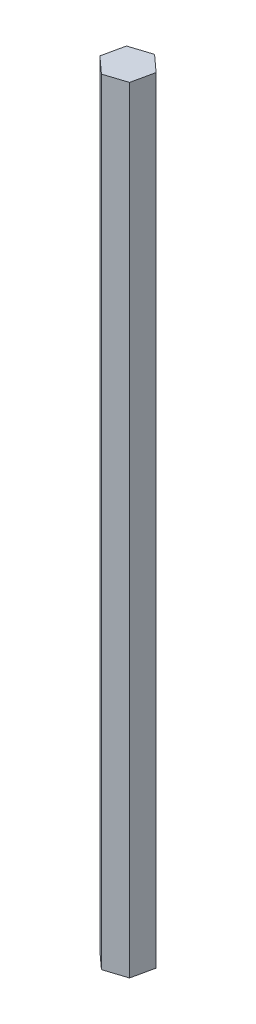
SolidWorks part; units mm, degrees
ref_plane "Front Plane" through (0, 0, 0) normal (0, 0, 1) x (1, 0, 0)
ref_plane "Top Plane" through (0, 0, 0) normal (0, 1, 0) x (1, 0, 0)
ref_plane "Right Plane" through (0, 0, 0) normal (1, 0, 0) x (0, 0, -1)
sketch "Sketch2" plane through (0, 0, 0) normal (0, 1, 0) x (1, 0, 0)
  line L1 (2.1373, -1.9404) -> (2.7491, 0.8807)
  line L2 (2.7491, 0.8807) -> (0.6118, 2.8212)
  line L3 (0.6118, 2.8212) -> (-2.1373, 1.9404)
  line L4 (-2.1373, 1.9404) -> (-2.7491, -0.8807)
  line L5 (-2.7491, -0.8807) -> (-0.6118, -2.8212)
  line L6 (-0.6118, -2.8212) -> (2.1373, -1.9404)
  circle A0 centre (0, 0) radius 2.5 construction
extrude "Boss-Extrude1" add sketch "Sketch2" along normal blind 127
sketch "Sketch3" plane through (0, 0, 0) normal (0, -1, 0) x (1, 0, 0)
  line L1 (-13.2192, 9.8568) -> (6.9753, 9.8568)
  line L2 (-13.2192, 9.8568) -> (-13.2192, -8.314)
  line L3 (-13.2192, -8.314) -> (6.9753, -8.314)
  line L4 (6.9753, 9.8568) -> (6.9753, -8.314)
extrude "Cut-Extrude1" cut sketch "Sketch3" against normal blind 38.1
sketch "Sketch4" plane through (0, 38.1, 0) normal (0, -1, 0) x (1, 0, 0)
  line L1 (0.6118, -2.8212) -> (2.7491, -0.8807)
  line L2 (2.7491, -0.8807) -> (2.1373, 1.9404)
  line L3 (2.1373, 1.9404) -> (-0.6118, 2.8212)
  line L4 (-0.6118, 2.8212) -> (-2.7491, 0.8807)
  line L5 (-2.7491, 0.8807) -> (-2.1373, -1.9404)
  line L6 (-2.1373, -1.9404) -> (0.6118, -2.8212)
  circle A0 centre (0, 0) radius 2.5 construction
extrude "Boss-Extrude2" add sketch "Sketch4" along normal blind 2.54
sketch "Sketch5" plane through (0, 35.56, 0) normal (0, -1, 0) x (1, 0, 0)
  line L1 (-18.607, 10.1377) -> (15.9105, 10.1377)
  line L2 (-18.607, 10.1377) -> (-18.607, -12.2028)
  line L3 (-18.607, -12.2028) -> (15.9105, -12.2028)
  line L4 (15.9105, 10.1377) -> (15.9105, -12.2028)
extrude "Cut-Extrude2" cut sketch "Sketch5" against normal blind 50
sketch "Sketch7" plane through (0, 85.56, 0) normal (0, -1, 0) x (1, 0, 0)
  line L1 (0.6118, -2.8212) -> (2.7491, -0.8807)
  line L2 (2.7491, -0.8807) -> (2.1373, 1.9404)
  line L3 (2.1373, 1.9404) -> (-0.6118, 2.8212)
  line L4 (-0.6118, 2.8212) -> (-2.7491, 0.8807)
  line L5 (-2.7491, 0.8807) -> (-2.1373, -1.9404)
  line L6 (-2.1373, -1.9404) -> (0.6118, -2.8212)
  circle A0 centre (0, 0) radius 2.5 construction
extrude "Boss-Extrude3" add sketch "Sketch7" along normal blind 25
sketch "Sketch8" plane through (0, 60.56, 0) normal (0, -1, 0) x (1, 0, 0)
  line L1 (0.6118, -2.8212) -> (2.7491, -0.8807)
  line L2 (2.7491, -0.8807) -> (2.1373, 1.9404)
  line L3 (2.1373, 1.9404) -> (-0.6118, 2.8212)
  line L4 (-0.6118, 2.8212) -> (-2.7491, 0.8807)
  line L5 (-2.7491, 0.8807) -> (-2.1373, -1.9404)
  line L6 (-2.1373, -1.9404) -> (0.6118, -2.8212)
  circle A0 centre (0, 0) radius 2.5 construction
extrude "Boss-Extrude4" add sketch "Sketch8" along normal blind 13.5
sketch "Sketch9" plane through (0, 47.06, 0) normal (0, -1, 0) x (1, 0, 0)
  line L1 (0.6118, -2.8212) -> (2.7491, -0.8807)
  line L2 (2.7491, -0.8807) -> (2.1373, 1.9404)
  line L3 (2.1373, 1.9404) -> (-0.6118, 2.8212)
  line L4 (-0.6118, 2.8212) -> (-2.7491, 0.8807)
  line L5 (-2.7491, 0.8807) -> (-2.1373, -1.9404)
  line L6 (-2.1373, -1.9404) -> (0.6118, -2.8212)
  circle A0 centre (0, 0) radius 2.5 construction
extrude "Boss-Extrude5" add sketch "Sketch9" along normal blind 20.32
